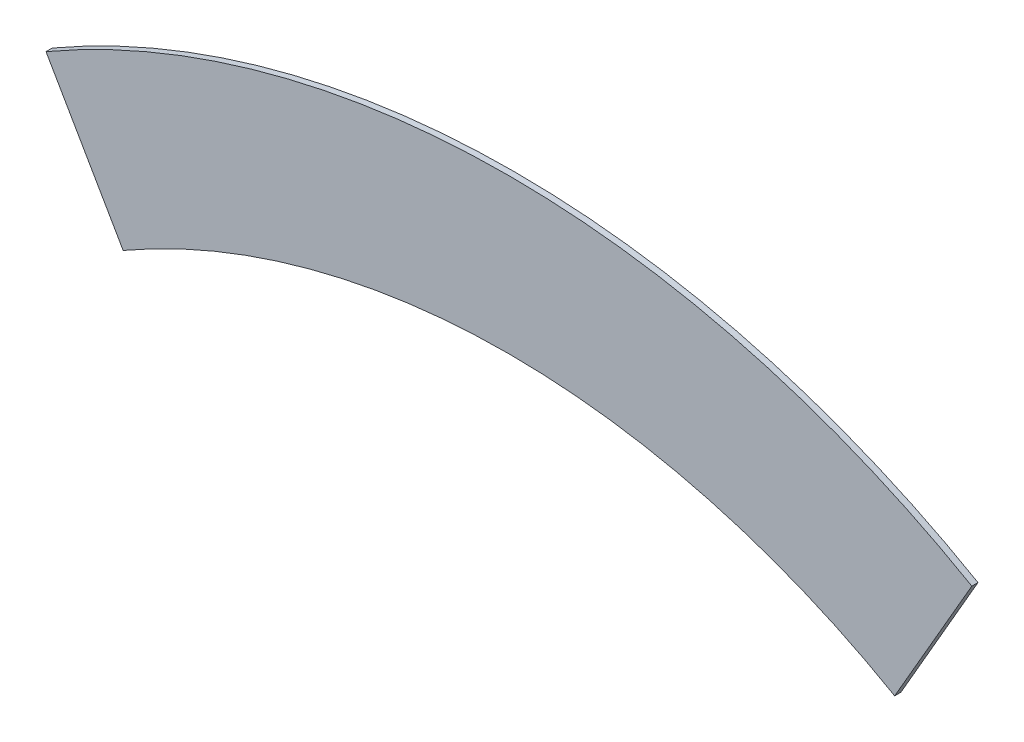
SolidWorks part; units mm, degrees
ref_plane "Plano frontal" through (0, 0, 0) normal (0, 0, 1) x (1, 0, 0)
ref_plane "Plano superior" through (0, 0, 0) normal (0, 1, 0) x (1, 0, 0)
ref_plane "Plano direito" through (0, 0, 0) normal (1, 0, 0) x (0, 0, -1)
sketch "Esboço1" plane through (0, 0, 0) normal (0, 0, 1) x (1, 0, 0)
  line L4 (-12.5, 21.6506) -> (-15, 25.9808)
  line L5 (12.5, 21.6506) -> (15, 25.9808)
  arc A1 (12.5, 21.6506) -> (-12.5, 21.6506) centre (0, 0) ccw
  arc A2 (15, 25.9808) -> (-15, 25.9808) centre (0, 0) ccw
  point P8 (0, -35)
  dimension "D2" = 50
extrude "Ressalto-extrusão1" add sketch "Esboço1" along normal blind 0.2
